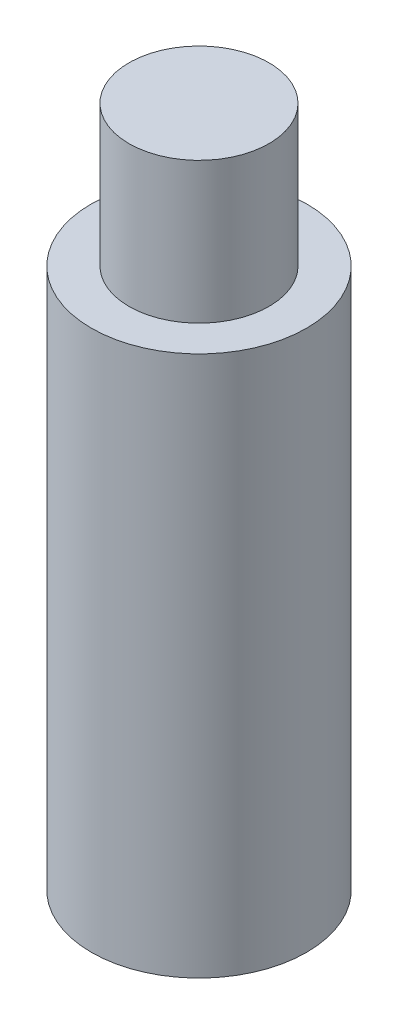
SolidWorks part; units mm, degrees
ref_plane "Front Plane" through (0, 0, 0) normal (0, 0, 1) x (1, 0, 0)
ref_plane "Top Plane" through (0, 0, 0) normal (0, 1, 0) x (1, 0, 0)
ref_plane "Right Plane" through (0, 0, 0) normal (1, 0, 0) x (0, 0, -1)
sketch "Sketch1" plane through (0, 0, 0) normal (0, 1, 0) x (1, 0, 0)
  circle A0 centre (0, 0) radius 11.45
  dimension "D1" = 22.9
extrude "Boss-Extrude1" add sketch "Sketch1" along normal blind 57.5
sketch "Sketch2" plane through (0, 57.5, 0) normal (0, 1, 0) x (1, 0, 0)
  circle A0 centre (0, 0) radius 7.45
  dimension "D1" = 14.9
extrude "Boss-Extrude2" add sketch "Sketch2" along normal blind 15
sketch "Sketch3" plane through (0, 0, 0) normal (0, -1, 0) x (1, 0, 0)
  line L0 (-3.4749, 2.0803) -> (1.547, 3.7429)
  circle A0 centre (0, 0) radius 4.05
  dimension "D1" = 8.1
  dimension "D2" = 5.29
extrude "Cut-Extrude1" cut sketch "Sketch3" against normal blind 15 contours L0 A0
